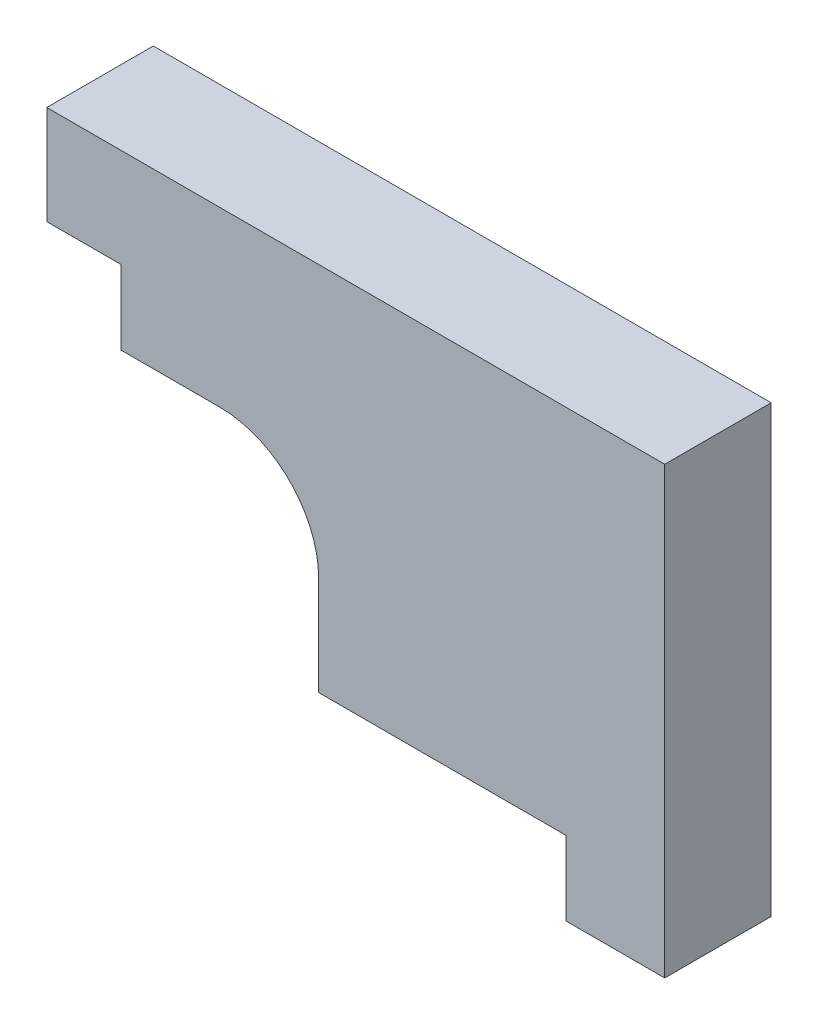
SolidWorks part; units mm, degrees
ref_plane "Front Plane" through (0, 0, 0) normal (0, 0, 1) x (1, 0, 0)
ref_plane "Top Plane" through (0, 0, 0) normal (0, 1, 0) x (1, 0, 0)
ref_plane "Right Plane" through (0, 0, 0) normal (1, 0, 0) x (0, 0, -1)
sketch "Sketch1" plane through (0, 0, 0) normal (0, 0, 1) x (1, 0, 0)
  line L0 (150, -130) -> (150, 130) construction
  line L1 (130, 150) -> (-130, 150) construction
  line L2 (150, 110) -> (150, 130)
  line L3 (130, 150) -> (110, 150)
  line L4 (110, 150) -> (110, 165)
  line L5 (110, 165) -> (95, 165)
  line L7 (220, 95) -> (200, 95)
  line L8 (95, 165) -> (95, 185)
  line L9 (95, 185) -> (220, 185)
  line L10 (220, 185) -> (220, 95)
  line L11 (200, 95) -> (200, 110)
  line L12 (200, 110) -> (150, 110)
  line L13 (110, 150) -> (-130, 150) construction
  line L14 (150, -130) -> (150, 110) construction
  arc A0 (150, 130) -> (130, 150) centre (130, 130) ccw construction
  arc A1 (150, 130) -> (130, 150) centre (130, 130) ccw
  dimension "D1" = 15
  dimension "D2" = 20
  dimension "D3" = 20
  dimension "D4" = 20
  dimension "D5" = 15
  dimension "D6" = 15
  dimension "D7" = 50
  dimension "D8" = 20
extrude "Boss-Extrude1" add sketch "Sketch1" against normal up to vertex (21.5428 mm away)
